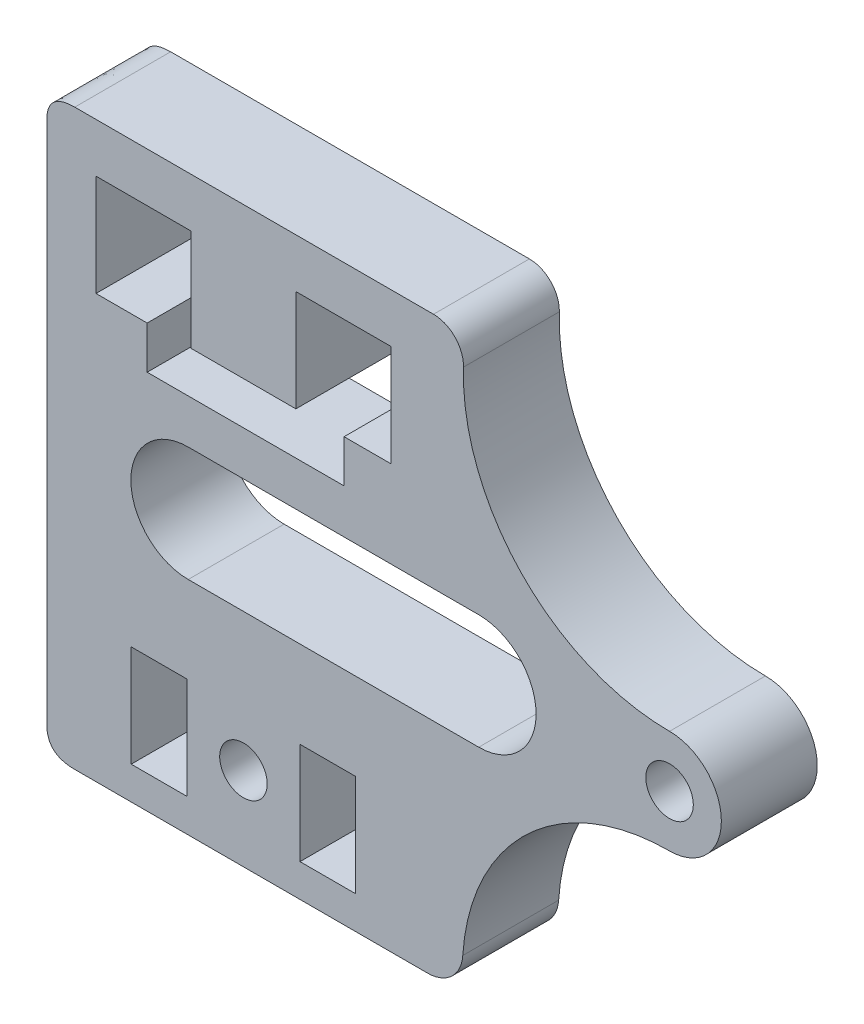
SolidWorks part; units mm, degrees
ref_plane "Front Plane" through (0, 0, 0) normal (0, 0, 1) x (1, 0, 0)
ref_plane "Top Plane" through (0, 0, 0) normal (0, 1, 0) x (1, 0, 0)
ref_plane "Right Plane" through (0, 0, 0) normal (1, 0, 0) x (0, 0, -1)
sketch "Sketch1" plane through (0, 0, 0) normal (0, 0, 1) x (1, 0, 0)
  line L0 (405.6988, 552.3389) -> (405.6988, 554.9389)
  line L1 (396.361, 554.9389) -> (402.7571, 554.9389)
  line L2 (393.683, 554.9389) -> (393.683, 552.3389)
  line L3 (393.683, 552.3389) -> (405.6988, 552.3389)
  line L4 (390.561, 561.1389) -> (390.561, 554.9389)
  line L5 (393.683, 554.9389) -> (390.561, 554.9389)
  line L6 (396.361, 561.1389) -> (390.561, 561.1389)
  line L7 (396.361, 554.9389) -> (396.361, 561.1389)
  line L8 (405.6988, 554.9389) -> (408.5571, 554.9389)
  line L9 (408.5571, 554.9389) -> (408.5571, 561.1389)
  line L10 (402.7571, 561.1389) -> (402.7571, 554.9389)
  line L11 (408.5571, 561.1389) -> (402.7571, 561.1389)
  line L12 (392.709, 537.3389) -> (392.709, 531.1389)
  line L13 (392.709, 531.1389) -> (396.109, 531.1389)
  line L14 (396.109, 537.3389) -> (392.709, 537.3389)
  line L15 (396.109, 531.1389) -> (396.109, 537.3389)
  line L16 (403.009, 531.1389) -> (406.4091, 531.1389)
  line L17 (406.4091, 531.1389) -> (406.4091, 537.3389)
  line L18 (403.009, 537.3389) -> (403.009, 531.1389)
  line L19 (406.4091, 537.3389) -> (403.009, 537.3389)
  line L20 (389.2659, 564.1389) -> (411.156, 564.1389)
  line L21 (387.561, 562.4358) -> (387.561, 530.842)
  line L22 (389.2659, 529.1389) -> (410.802, 529.1389)
  line L23 (-606.039, 561.1389) -> (49393.961, 561.1389) construction
  line L24 (396.1883, 549.6389) -> (413.9157, 549.6389)
  line L25 (396.1883, 542.6389) -> (413.9157, 542.6389)
  line L26 (-600.441, 546.1389) -> (49399.559, 546.1389) construction
  line L27 (398.109, 534.2389) -> (396.109, 534.2389) construction
  line L28 (401.009, 534.2389) -> (403.009, 534.2389) construction
  line L29 (399.559, -466.6171) -> (399.559, 49533.3829) construction
  line L30 (425.559, -455.7473) -> (425.559, 49544.2527) construction
  line L31 (-599.1986, 531.1389) -> (49400.8014, 531.1389) construction
  line L32 (421.9074, 546.1389) -> (421.9074, 531.1389) construction
  line L33 (421.9074, 546.1389) -> (421.9074, 561.1389) construction
  circle A0 centre (425.559, 546.1389) radius 1.45
  arc A1 (396.1883, 549.6389) -> (396.1883, 542.6389) centre (396.1883, 546.1389) ccw
  circle A2 centre (399.559, 534.2389) radius 1.45
  arc A3 (412.9415, 531.1453) -> (425.559, 542.9773) centre (425.559, 530.3337) cw
  arc A4 (412.983, 562.2567) -> (425.559, 549.3005) centre (425.559, 561.8822) ccw
  arc A5 (425.559, 549.3005) -> (425.559, 542.9773) centre (425.559, 546.1389) cw
  arc A7 (413.9157, 549.6389) -> (413.9157, 542.6389) centre (413.9157, 546.1389) cw
  arc A8 (410.802, 529.1389) -> (412.9415, 531.1453) centre (410.802, 531.2829) ccw
  arc A9 (411.156, 564.1389) -> (412.983, 562.2567) centre (411.156, 562.3111) cw
  spline S36 degree 2 poles (387.561, 562.4358) (387.4672, 564.1389) (389.2659, 564.1389) knots 0 0 0 1 1 1
  spline S37 degree 2 poles (387.561, 530.842) (387.4672, 529.1389) (389.2659, 529.1389) knots 0 0 0 1 1 1
  point P26 (399.559, 546.1389)
  point P30 (399.559, 554.9389)
  dimension "D5" = 2.9
  dimension "D1" = 6.2
  dimension "D2" = 3.4
  dimension "D3" = 5.8
  dimension "D4" = 2.6
  dimension "D6" = 2
  dimension "D7" = 30
  dimension "D8" = 2
  dimension "D9" = 3
  dimension "D10" = 3
  dimension "D11" = 26
extrude "Boss-Extrude2" add sketch "Sketch1" along normal blind 5.85
